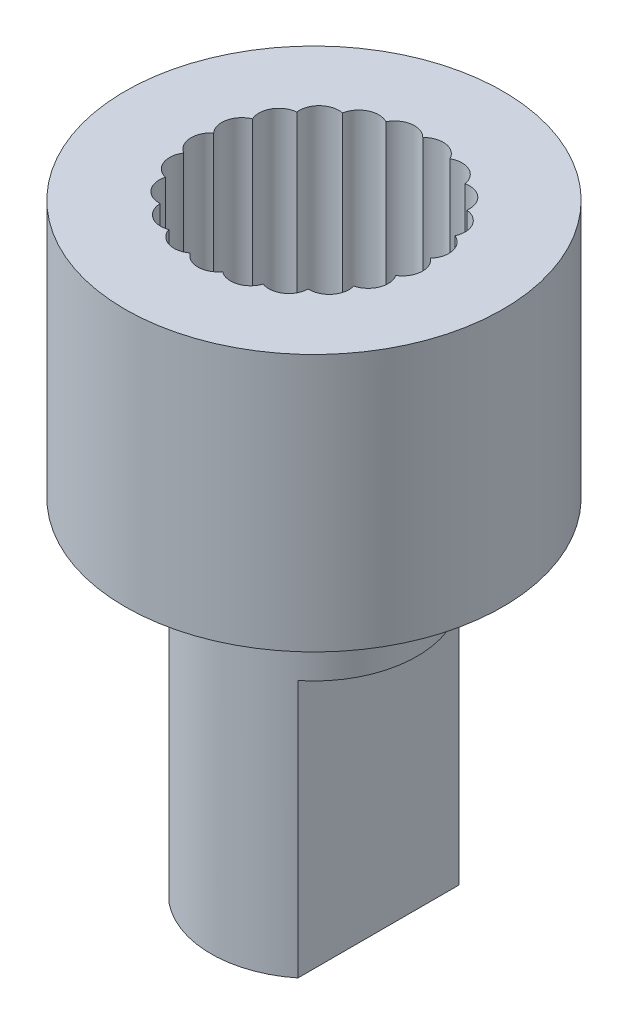
SolidWorks part; units mm, degrees
ref_plane "Front Plane" through (0, 0, 0) normal (0, 0, 1) x (1, 0, 0)
ref_plane "Top Plane" through (0, 0, 0) normal (0, 1, 0) x (1, 0, 0)
ref_plane "Right Plane" through (0, 0, 0) normal (1, 0, 0) x (0, 0, -1)
sketch "Sketch1" plane through (0, 0, 0) normal (0, 1, 0) x (1, 0, 0)
  line L0 (0, 0) -> (0, 4.4464) construction
  line L1 (0, 0) -> (0.6627, 4.3968) construction
  line L2 (0, 0) -> (1.3106, 4.2489) construction
  line L3 (0, 0) -> (1.9292, 4.0061) construction
  line L4 (0, 0) -> (2.5048, 3.6738) construction
  line L5 (0, 0) -> (3.0243, 3.2595) construction
  line L6 (0, 0) -> (3.4764, 2.7723) construction
  line L7 (0, 0) -> (3.8507, 2.2232) construction
  line L8 (0, 0) -> (4.1391, 1.6245) construction
  line L9 (0, 0) -> (4.3349, 0.9894) construction
  line L10 (0, 0) -> (4.434, 0.3323) construction
  line L11 (0, 0) -> (4.434, -0.3323) construction
  line L12 (0, 0) -> (4.3349, -0.9894) construction
  line L13 (0, 0) -> (4.1391, -1.6245) construction
  line L14 (0, 0) -> (3.8507, -2.2232) construction
  line L15 (0, 0) -> (3.4764, -2.7723) construction
  line L16 (0, 0) -> (3.0243, -3.2595) construction
  line L17 (0, 0) -> (2.5048, -3.6738) construction
  line L18 (0, 0) -> (1.9292, -4.0061) construction
  line L19 (0, 0) -> (1.3106, -4.2489) construction
  line L20 (0, 0) -> (0.6627, -4.3968) construction
  line L21 (0, 0) -> (0, -4.4464) construction
  line L22 (0, 0) -> (-0.6627, -4.3968) construction
  line L23 (0, 0) -> (-1.3106, -4.2489) construction
  line L24 (0, 0) -> (-1.9292, -4.0061) construction
  line L25 (0, 0) -> (-2.5048, -3.6738) construction
  line L26 (0, 0) -> (-3.0243, -3.2595) construction
  line L27 (0, 0) -> (-3.4764, -2.7723) construction
  line L28 (0, 0) -> (-3.8507, -2.2232) construction
  line L29 (0, 0) -> (-4.1391, -1.6245) construction
  line L30 (0, 0) -> (-4.3349, -0.9894) construction
  line L31 (0, 0) -> (-4.434, -0.3323) construction
  line L32 (0, 0) -> (-4.434, 0.3323) construction
  line L33 (0, 0) -> (-4.3349, 0.9894) construction
  line L34 (0, 0) -> (-4.1391, 1.6245) construction
  line L35 (0, 0) -> (-3.8507, 2.2232) construction
  line L36 (0, 0) -> (-3.4764, 2.7723) construction
  line L37 (0, 0) -> (-3.0243, 3.2595) construction
  line L38 (0, 0) -> (-2.5048, 3.6738) construction
  line L39 (0, 0) -> (-1.9292, 4.0061) construction
  line L40 (0, 0) -> (-1.3106, 4.2489) construction
  line L41 (0, 0) -> (-0.6627, 4.3968) construction
  circle A1 centre (0, 0) radius 2.45 construction
  circle A5 centre (0, 0) radius 3.95
  circle A14 centre (0, 0) radius 2.2653 construction
  arc A22 (-0.1666, 2.3451) -> (0, 2.2653) centre (0, 2.479) ccw
  arc A23 (-0.1666, 2.3451) -> (-0.532, 2.2901) centre (-0.3333, 2.2113) ccw
  arc A24 (-0.6677, 2.1646) -> (-0.532, 2.2901) centre (-0.7307, 2.3689) ccw
  arc A25 (0, 2.2653) -> (0.1666, 2.3451) centre (0, 2.479) ccw
  arc A26 (0.532, 2.2901) -> (0.1666, 2.3451) centre (0.3333, 2.2113) ccw
  arc A27 (0.532, 2.2901) -> (0.6677, 2.1646) centre (0.7307, 2.3689) ccw
  arc A28 (0.6677, 2.1646) -> (0.8505, 2.1918) centre (0.7307, 2.3689) ccw
  arc A29 (1.1834, 2.0315) -> (0.8505, 2.1918) centre (0.9703, 2.0148) ccw
  arc A30 (1.1834, 2.0315) -> (1.2761, 1.8716) centre (1.3965, 2.0483) ccw
  arc A31 (1.2761, 1.8716) -> (1.4588, 1.8438) centre (1.3965, 2.0483) ccw
  arc A32 (1.7296, 1.5925) -> (1.4588, 1.8438) centre (1.521, 1.6393) ccw
  arc A33 (1.7296, 1.5925) -> (1.7711, 1.4124) centre (1.9382, 1.5456) ccw
  arc A34 (1.7711, 1.4124) -> (1.9374, 1.3319) centre (1.9382, 1.5456) ccw
  arc A35 (2.1221, 1.0119) -> (1.9374, 1.3319) centre (1.9366, 1.1181) ccw
  arc A36 (2.1221, 1.0119) -> (2.1087, 0.8276) centre (2.3077, 0.9057) ccw
  arc A37 (2.1087, 0.8276) -> (2.2439, 0.7016) centre (2.3077, 0.9057) ccw
  arc A38 (2.3261, 0.3414) -> (2.2439, 0.7016) centre (2.1802, 0.4976) ccw
  arc A39 (2.3261, 0.3414) -> (2.2589, 0.1693) centre (2.4721, 0.1853) ccw
  arc A40 (2.2589, 0.1693) -> (2.351, 0.0091) centre (2.4721, 0.1853) ccw
  arc A41 (2.3234, -0.3594) -> (2.351, 0.0091) centre (2.23, -0.1671) ccw
  arc A42 (2.3234, -0.3594) -> (2.2085, -0.5041) centre (2.4169, -0.5516) ccw
  arc A43 (2.2085, -0.5041) -> (2.2493, -0.6843) centre (2.4169, -0.5516) ccw
  arc A44 (2.1143, -1.0283) -> (2.2493, -0.6843) centre (2.0817, -0.817) ccw
  arc A45 (2.1143, -1.0283) -> (1.9618, -1.1326) centre (2.1469, -1.2395) ccw
  arc A46 (1.9618, -1.1326) -> (1.9476, -1.3169) centre (2.1469, -1.2395) ccw
  arc A47 (1.7173, -1.6058) -> (1.9476, -1.3169) centre (1.7484, -1.3943) ccw
  arc A48 (1.7173, -1.6058) -> (1.5408, -1.6606) centre (1.6862, -1.8173) ccw
  arc A49 (1.5408, -1.6606) -> (1.4729, -1.8325) centre (1.6862, -1.8173) ccw
  arc A50 (1.1677, -2.0406) -> (1.4729, -1.8325) centre (1.2597, -1.8477) ccw
  arc A51 (1.1677, -2.0406) -> (0.9829, -2.0409) centre (1.0756, -2.2335) ccw
  arc A52 (0.9829, -2.0409) -> (0.8674, -2.1852) centre (1.0756, -2.2335) ccw
  arc A53 (0.5143, -2.2941) -> (0.8674, -2.1852) centre (0.6591, -2.1369) ccw
  arc A54 (0.5143, -2.2941) -> (0.3376, -2.24) centre (0.3695, -2.4513) ccw
  arc A55 (0.3376, -2.24) -> (0.1847, -2.3438) centre (0.3695, -2.4513) ccw
  arc A56 (-0.1847, -2.3438) -> (0.1847, -2.3438) centre (0, -2.2362) ccw
  arc A57 (-0.1847, -2.3438) -> (-0.3376, -2.24) centre (-0.3695, -2.4513) ccw
  arc A58 (-0.3376, -2.24) -> (-0.5143, -2.2941) centre (-0.3695, -2.4513) ccw
  arc A59 (-0.8674, -2.1852) -> (-0.5143, -2.2941) centre (-0.6591, -2.1369) ccw
  arc A60 (-0.8674, -2.1852) -> (-0.9829, -2.0409) centre (-1.0756, -2.2335) ccw
  arc A61 (-0.9829, -2.0409) -> (-1.1677, -2.0406) centre (-1.0756, -2.2335) ccw
  arc A62 (-1.4729, -1.8325) -> (-1.1677, -2.0406) centre (-1.2597, -1.8477) ccw
  arc A63 (-1.4729, -1.8325) -> (-1.5408, -1.6606) centre (-1.6862, -1.8173) ccw
  arc A64 (-1.5408, -1.6606) -> (-1.7173, -1.6058) centre (-1.6862, -1.8173) ccw
  arc A65 (-1.9476, -1.3169) -> (-1.7173, -1.6058) centre (-1.7484, -1.3943) ccw
  arc A66 (-1.9476, -1.3169) -> (-1.9618, -1.1326) centre (-2.1469, -1.2395) ccw
  arc A67 (-1.9618, -1.1326) -> (-2.1143, -1.0283) centre (-2.1469, -1.2395) ccw
  arc A68 (-2.2493, -0.6843) -> (-2.1143, -1.0283) centre (-2.0817, -0.817) ccw
  arc A69 (-2.2493, -0.6843) -> (-2.2085, -0.5041) centre (-2.4169, -0.5516) ccw
  arc A70 (-2.2085, -0.5041) -> (-2.3234, -0.3594) centre (-2.4169, -0.5516) ccw
  arc A71 (-2.351, 0.0091) -> (-2.3234, -0.3594) centre (-2.23, -0.1671) ccw
  arc A72 (-2.351, 0.0091) -> (-2.2589, 0.1693) centre (-2.4721, 0.1853) ccw
  arc A73 (-2.2589, 0.1693) -> (-2.3261, 0.3414) centre (-2.4721, 0.1853) ccw
  arc A74 (-2.2439, 0.7016) -> (-2.3261, 0.3414) centre (-2.1802, 0.4976) ccw
  arc A75 (-2.2439, 0.7016) -> (-2.1087, 0.8276) centre (-2.3077, 0.9057) ccw
  arc A76 (-2.1087, 0.8276) -> (-2.1221, 1.0119) centre (-2.3077, 0.9057) ccw
  arc A77 (-1.9374, 1.3319) -> (-2.1221, 1.0119) centre (-1.9366, 1.1181) ccw
  arc A78 (-1.9374, 1.3319) -> (-1.7711, 1.4124) centre (-1.9382, 1.5456) ccw
  arc A79 (-1.7711, 1.4124) -> (-1.7296, 1.5925) centre (-1.9382, 1.5456) ccw
  arc A80 (-1.4588, 1.8438) -> (-1.7296, 1.5925) centre (-1.521, 1.6393) ccw
  arc A81 (-1.4588, 1.8438) -> (-1.2761, 1.8716) centre (-1.3965, 2.0483) ccw
  arc A82 (-1.2761, 1.8716) -> (-1.1834, 2.0315) centre (-1.3965, 2.0483) ccw
  arc A83 (-0.8505, 2.1918) -> (-1.1834, 2.0315) centre (-0.9703, 2.0148) ccw
  arc A84 (-0.8505, 2.1918) -> (-0.6677, 2.1646) centre (-0.7307, 2.3689) ccw
  point P27 (0, 0)
  point P50 (0, 0)
  point P198 (0, 0)
  dimension "D1" = 1.5
  dimension "D2" = 4.9
  dimension "D3" = 42
  dimension "D4" = 2.2362
  dimension "D5" = 4.5305
  dimension "D6" = 4.5305
  dimension "D7" = 21
extrude "Boss-Extrude1" add sketch "Sketch1" along normal blind 4
sketch "Sketch2" plane through (0, 0, 0) normal (0, -1, 0) x (1, 0, 0)
  circle A0 centre (0, 0) radius 4.4
  dimension "D1" = 8.8
extrude "Boss-Extrude2" add sketch "Sketch2" along normal blind 2
sketch "Sketch4" plane through (0, -2, 0) normal (0, -1, 0) x (1, 0, 0)
  circle A0 centre (0, 0) radius 2.4
  dimension "D1" = 4.8
extrude "Boss-Extrude3" add sketch "Sketch4" along normal blind 2
sketch "Sketch5" plane through (0, -4, 0) normal (0, -1, 0) x (1, 0, 0)
  line L2 (-1.5, 1.8735) -> (-1.5, -1.8735)
  line L4 (1.5, 1.8735) -> (1.5, -1.8735)
  line L5 (-1.1513, 2.1058) -> (1.1513, -2.1058) construction
  line L6 (-1.1513, -2.1058) -> (1.1513, 2.1058) construction
  circle A0 centre (0, 0) radius 2.4
  point P0 (0, 0)
  circle M3 centre (0, 0) radius 2.4
extrude "Boss-Extrude4" add sketch "Sketch5" along normal blind 6 contours L4 L2 M3
sketch "Sketch6" plane through (0, 0, 0) normal (0, 1, 0) x (1, 0, 0)
  circle A0 centre (0, 0) radius 4.4
  circle A1 centre (0, 0) radius 3.95
extrude "Boss-Extrude5" add sketch "Sketch6" along normal blind 4
sketch "Sketch8" plane through (0, 4, 0) normal (0, 1, 0) x (1, 0, 0)
  line L0 (2.3886, 0.5452) -> (2.3409, 0.7542)
  line L1 (2.3886, 0.5452) -> (2.6323, 0.6008)
  arc A0 (2.3261, 0.3414) -> (2.2439, 0.7016) centre (2.1802, 0.4976) ccw construction
  arc A43 (0, 2.5337) -> (0, 2.5337) centre (0, 2.5337) ccw
  arc A44 (0.7468, 2.4212) -> (0, 2.5337) centre (0.3333, 2.2113) ccw
  arc A45 (0.7468, 2.4212) -> (0.7468, 2.4212) centre (0.7468, 2.4212) ccw
  arc A46 (1.4273, 2.0935) -> (0.7468, 2.4212) centre (0.9703, 2.0148) ccw
  arc A47 (1.4273, 2.0935) -> (1.4273, 2.0935) centre (1.4273, 2.0935) ccw
  arc A48 (1.981, 1.5798) -> (1.4273, 2.0935) centre (1.521, 1.6393) ccw
  arc A49 (1.981, 1.5798) -> (1.981, 1.5798) centre (1.981, 1.5798) ccw
  arc A50 (2.3586, 0.9257) -> (1.981, 1.5798) centre (1.9366, 1.1181) ccw
  arc A51 (2.3586, 0.9257) -> (2.3586, 0.9257) centre (2.3586, 0.9257) ccw
  arc A52 (2.5267, 0.1893) -> (2.3586, 0.9257) centre (2.1802, 0.4976) ccw
  arc A53 (2.5267, 0.1893) -> (2.5267, 0.1893) centre (2.5267, 0.1893) ccw
  arc A54 (2.4702, -0.5638) -> (2.5267, 0.1893) centre (2.23, -0.1671) ccw
  arc A55 (2.4702, -0.5638) -> (2.4702, -0.5638) centre (2.4702, -0.5638) ccw
  arc A56 (2.1943, -1.2669) -> (2.4702, -0.5638) centre (2.0817, -0.817) ccw
  arc A57 (2.1943, -1.2669) -> (2.1943, -1.2669) centre (2.1943, -1.2669) ccw
  arc A58 (1.7234, -1.8574) -> (2.1943, -1.2669) centre (1.7484, -1.3943) ccw
  arc A59 (1.7234, -1.8574) -> (1.7234, -1.8574) centre (1.7234, -1.8574) ccw
  arc A60 (1.0993, -2.2828) -> (1.7234, -1.8574) centre (1.2597, -1.8477) ccw
  arc A61 (1.0993, -2.2828) -> (1.0993, -2.2828) centre (1.0993, -2.2828) ccw
  arc A62 (0.3776, -2.5054) -> (1.0993, -2.2828) centre (0.6591, -2.1369) ccw
  arc A63 (0.3776, -2.5054) -> (0.3776, -2.5054) centre (0.3776, -2.5054) ccw
  arc A64 (-0.3776, -2.5054) -> (0.3776, -2.5054) centre (0, -2.2362) ccw
  arc A65 (-0.3776, -2.5054) -> (-0.3776, -2.5054) centre (-0.3776, -2.5054) ccw
  arc A66 (-1.0993, -2.2828) -> (-0.3776, -2.5054) centre (-0.6591, -2.1369) ccw
  arc A67 (-1.0993, -2.2828) -> (-1.0993, -2.2828) centre (-1.0993, -2.2828) ccw
  arc A68 (-1.7234, -1.8574) -> (-1.0993, -2.2828) centre (-1.2597, -1.8477) ccw
  arc A69 (-1.7234, -1.8574) -> (-1.7234, -1.8574) centre (-1.7234, -1.8574) ccw
  arc A70 (-2.1943, -1.2669) -> (-1.7234, -1.8574) centre (-1.7484, -1.3943) ccw
  arc A71 (-2.1943, -1.2669) -> (-2.1943, -1.2669) centre (-2.1943, -1.2669) ccw
  arc A72 (-2.4702, -0.5638) -> (-2.1943, -1.2669) centre (-2.0817, -0.817) ccw
  arc A73 (-2.4702, -0.5638) -> (-2.4702, -0.5638) centre (-2.4702, -0.5638) ccw
  arc A74 (-2.5267, 0.1893) -> (-2.4702, -0.5638) centre (-2.23, -0.1671) ccw
  arc A75 (-2.5267, 0.1893) -> (-2.5267, 0.1893) centre (-2.5267, 0.1893) ccw
  arc A76 (-2.3586, 0.9257) -> (-2.5267, 0.1893) centre (-2.1802, 0.4976) ccw
  arc A77 (-2.3586, 0.9257) -> (-2.3586, 0.9257) centre (-2.3586, 0.9257) ccw
  arc A78 (-1.981, 1.5798) -> (-2.3586, 0.9257) centre (-1.9366, 1.1181) ccw
  arc A79 (-1.981, 1.5798) -> (-1.981, 1.5798) centre (-1.981, 1.5798) ccw
  arc A80 (-1.4273, 2.0935) -> (-1.981, 1.5798) centre (-1.521, 1.6393) ccw
  arc A81 (-1.4273, 2.0935) -> (-1.4273, 2.0935) centre (-1.4273, 2.0935) ccw
  arc A82 (-0.7468, 2.4212) -> (-1.4273, 2.0935) centre (-0.9703, 2.0148) ccw
  arc A83 (-0.7468, 2.4212) -> (-0.7468, 2.4212) centre (-0.7468, 2.4212) ccw
  arc A84 (0, 2.5337) -> (-0.7468, 2.4212) centre (-0.3333, 2.2113) ccw
  arc A85 (-0.1666, 2.3451) -> (0.1666, 2.3451) centre (0, 2.479) ccw
  arc A86 (-0.1666, 2.3451) -> (-0.532, 2.2901) centre (-0.3333, 2.2113) ccw
  arc A87 (-0.8505, 2.1918) -> (-0.532, 2.2901) centre (-0.7307, 2.3689) ccw
  arc A88 (-0.8505, 2.1918) -> (-1.1834, 2.0315) centre (-0.9703, 2.0148) ccw
  arc A89 (-1.4588, 1.8438) -> (-1.1834, 2.0315) centre (-1.3965, 2.0483) ccw
  arc A90 (-1.4588, 1.8438) -> (-1.7296, 1.5925) centre (-1.521, 1.6393) ccw
  arc A91 (-1.9374, 1.3319) -> (-1.7296, 1.5925) centre (-1.9382, 1.5456) ccw
  arc A92 (-1.9374, 1.3319) -> (-2.1221, 1.0119) centre (-1.9366, 1.1181) ccw
  arc A93 (-2.2439, 0.7016) -> (-2.1221, 1.0119) centre (-2.3077, 0.9057) ccw
  arc A94 (-2.2439, 0.7016) -> (-2.3261, 0.3414) centre (-2.1802, 0.4976) ccw
  arc A95 (-2.351, 0.0091) -> (-2.3261, 0.3414) centre (-2.4721, 0.1853) ccw
  arc A96 (-2.351, 0.0091) -> (-2.3234, -0.3594) centre (-2.23, -0.1671) ccw
  arc A97 (-2.2493, -0.6843) -> (-2.3234, -0.3594) centre (-2.4169, -0.5516) ccw
  arc A98 (-2.2493, -0.6843) -> (-2.1143, -1.0283) centre (-2.0817, -0.817) ccw
  arc A99 (-1.9476, -1.3169) -> (-2.1143, -1.0283) centre (-2.1469, -1.2395) ccw
  arc A100 (-1.9476, -1.3169) -> (-1.7173, -1.6058) centre (-1.7484, -1.3943) ccw
  arc A101 (-1.4729, -1.8325) -> (-1.7173, -1.6058) centre (-1.6862, -1.8173) ccw
  arc A102 (-1.4729, -1.8325) -> (-1.1677, -2.0406) centre (-1.2597, -1.8477) ccw
  arc A103 (-0.8674, -2.1852) -> (-1.1677, -2.0406) centre (-1.0756, -2.2335) ccw
  arc A104 (-0.8674, -2.1852) -> (-0.5143, -2.2941) centre (-0.6591, -2.1369) ccw
  arc A105 (-0.1847, -2.3438) -> (-0.5143, -2.2941) centre (-0.3695, -2.4513) ccw
  arc A106 (-0.1847, -2.3438) -> (0.1847, -2.3438) centre (0, -2.2362) ccw
  arc A107 (0.5143, -2.2941) -> (0.1847, -2.3438) centre (0.3695, -2.4513) ccw
  arc A108 (0.5143, -2.2941) -> (0.8674, -2.1852) centre (0.6591, -2.1369) ccw
  arc A109 (1.1677, -2.0406) -> (0.8674, -2.1852) centre (1.0756, -2.2335) ccw
  arc A110 (1.1677, -2.0406) -> (1.4729, -1.8325) centre (1.2597, -1.8477) ccw
  arc A111 (1.7173, -1.6058) -> (1.4729, -1.8325) centre (1.6862, -1.8173) ccw
  arc A112 (1.7173, -1.6058) -> (1.9476, -1.3169) centre (1.7484, -1.3943) ccw
  arc A113 (2.1143, -1.0283) -> (1.9476, -1.3169) centre (2.1469, -1.2395) ccw
  arc A114 (2.1143, -1.0283) -> (2.2493, -0.6843) centre (2.0817, -0.817) ccw
  arc A115 (2.3234, -0.3594) -> (2.2493, -0.6843) centre (2.4169, -0.5516) ccw
  arc A116 (2.3234, -0.3594) -> (2.351, 0.0091) centre (2.23, -0.1671) ccw
  arc A117 (2.3261, 0.3414) -> (2.351, 0.0091) centre (2.4721, 0.1853) ccw
  arc A118 (2.3261, 0.3414) -> (2.2439, 0.7016) centre (2.1802, 0.4976) ccw
  arc A119 (2.1221, 1.0119) -> (2.2439, 0.7016) centre (2.3077, 0.9057) ccw
  arc A120 (2.1221, 1.0119) -> (1.9374, 1.3319) centre (1.9366, 1.1181) ccw
  arc A121 (1.7296, 1.5925) -> (1.9374, 1.3319) centre (1.9382, 1.5456) ccw
  arc A122 (1.7296, 1.5925) -> (1.4588, 1.8438) centre (1.521, 1.6393) ccw
  arc A123 (1.1834, 2.0315) -> (1.4588, 1.8438) centre (1.3965, 2.0483) ccw
  arc A124 (1.1834, 2.0315) -> (0.8505, 2.1918) centre (0.9703, 2.0148) ccw
  arc A125 (0.532, 2.2901) -> (0.8505, 2.1918) centre (0.7307, 2.3689) ccw
  arc A126 (0.532, 2.2901) -> (0.1666, 2.3451) centre (0.3333, 2.2113) ccw
  arc A127 (-0.1666, 2.3451) -> (0.1666, 2.3451) centre (0, 2.479) ccw
  arc A128 (-0.1666, 2.3451) -> (-0.532, 2.2901) centre (-0.3333, 2.2113) ccw
  arc A129 (-0.8505, 2.1918) -> (-0.532, 2.2901) centre (-0.7307, 2.3689) ccw
  arc A130 (-0.8505, 2.1918) -> (-1.1834, 2.0315) centre (-0.9703, 2.0148) ccw
  arc A131 (-1.4588, 1.8438) -> (-1.1834, 2.0315) centre (-1.3965, 2.0483) ccw
  arc A132 (-1.4588, 1.8438) -> (-1.7296, 1.5925) centre (-1.521, 1.6393) ccw
  arc A133 (-1.9374, 1.3319) -> (-1.7296, 1.5925) centre (-1.9382, 1.5456) ccw
  arc A134 (-1.9374, 1.3319) -> (-2.1221, 1.0119) centre (-1.9366, 1.1181) ccw
  arc A135 (-2.2439, 0.7016) -> (-2.1221, 1.0119) centre (-2.3077, 0.9057) ccw
  arc A136 (-2.2439, 0.7016) -> (-2.3261, 0.3414) centre (-2.1802, 0.4976) ccw
  arc A137 (-2.351, 0.0091) -> (-2.3261, 0.3414) centre (-2.4721, 0.1853) ccw
  arc A138 (-2.351, 0.0091) -> (-2.3234, -0.3594) centre (-2.23, -0.1671) ccw
  arc A139 (-2.2493, -0.6843) -> (-2.3234, -0.3594) centre (-2.4169, -0.5516) ccw
  arc A140 (-2.2493, -0.6843) -> (-2.1143, -1.0283) centre (-2.0817, -0.817) ccw
  arc A141 (-1.9476, -1.3169) -> (-2.1143, -1.0283) centre (-2.1469, -1.2395) ccw
  arc A142 (-1.9476, -1.3169) -> (-1.7173, -1.6058) centre (-1.7484, -1.3943) ccw
  arc A143 (-1.4729, -1.8325) -> (-1.7173, -1.6058) centre (-1.6862, -1.8173) ccw
  arc A144 (-1.4729, -1.8325) -> (-1.1677, -2.0406) centre (-1.2597, -1.8477) ccw
  arc A145 (-0.8674, -2.1852) -> (-1.1677, -2.0406) centre (-1.0756, -2.2335) ccw
  arc A146 (-0.8674, -2.1852) -> (-0.5143, -2.2941) centre (-0.6591, -2.1369) ccw
  arc A147 (-0.1847, -2.3438) -> (-0.5143, -2.2941) centre (-0.3695, -2.4513) ccw
  arc A148 (-0.1847, -2.3438) -> (0.1847, -2.3438) centre (0, -2.2362) ccw
  arc A149 (0.5143, -2.2941) -> (0.1847, -2.3438) centre (0.3695, -2.4513) ccw
  arc A150 (0.5143, -2.2941) -> (0.8674, -2.1852) centre (0.6591, -2.1369) ccw
  arc A151 (1.1677, -2.0406) -> (0.8674, -2.1852) centre (1.0756, -2.2335) ccw
  arc A152 (1.1677, -2.0406) -> (1.4729, -1.8325) centre (1.2597, -1.8477) ccw
  arc A153 (1.7173, -1.6058) -> (1.4729, -1.8325) centre (1.6862, -1.8173) ccw
  arc A154 (1.7173, -1.6058) -> (1.9476, -1.3169) centre (1.7484, -1.3943) ccw
  arc A155 (2.1143, -1.0283) -> (1.9476, -1.3169) centre (2.1469, -1.2395) ccw
  arc A156 (2.1143, -1.0283) -> (2.2493, -0.6843) centre (2.0817, -0.817) ccw
  arc A157 (2.3234, -0.3594) -> (2.2493, -0.6843) centre (2.4169, -0.5516) ccw
  arc A158 (2.3234, -0.3594) -> (2.351, 0.0091) centre (2.23, -0.1671) ccw
  arc A159 (2.3261, 0.3414) -> (2.351, 0.0091) centre (2.4721, 0.1853) ccw
  arc A160 (2.3261, 0.3414) -> (2.2439, 0.7016) centre (2.1802, 0.4976) ccw
  arc A161 (2.1221, 1.0119) -> (2.2439, 0.7016) centre (2.3077, 0.9057) ccw
  arc A162 (2.1221, 1.0119) -> (1.9374, 1.3319) centre (1.9366, 1.1181) ccw
  arc A163 (1.7296, 1.5925) -> (1.9374, 1.3319) centre (1.9382, 1.5456) ccw
  arc A164 (1.7296, 1.5925) -> (1.4588, 1.8438) centre (1.521, 1.6393) ccw
  arc A165 (1.1834, 2.0315) -> (1.4588, 1.8438) centre (1.3965, 2.0483) ccw
  arc A166 (1.1834, 2.0315) -> (0.8505, 2.1918) centre (0.9703, 2.0148) ccw
  arc A167 (0.532, 2.2901) -> (0.8505, 2.1918) centre (0.7307, 2.3689) ccw
  arc A168 (0.532, 2.2901) -> (0.1666, 2.3451) centre (0.3333, 2.2113) ccw
  dimension "D1" = 0
  dimension "D2" = 0.25
extrude "Cut-Extrude1" cut sketch "Sketch8" against normal blind 4
equation "\"r0.247\"=0.713093"
